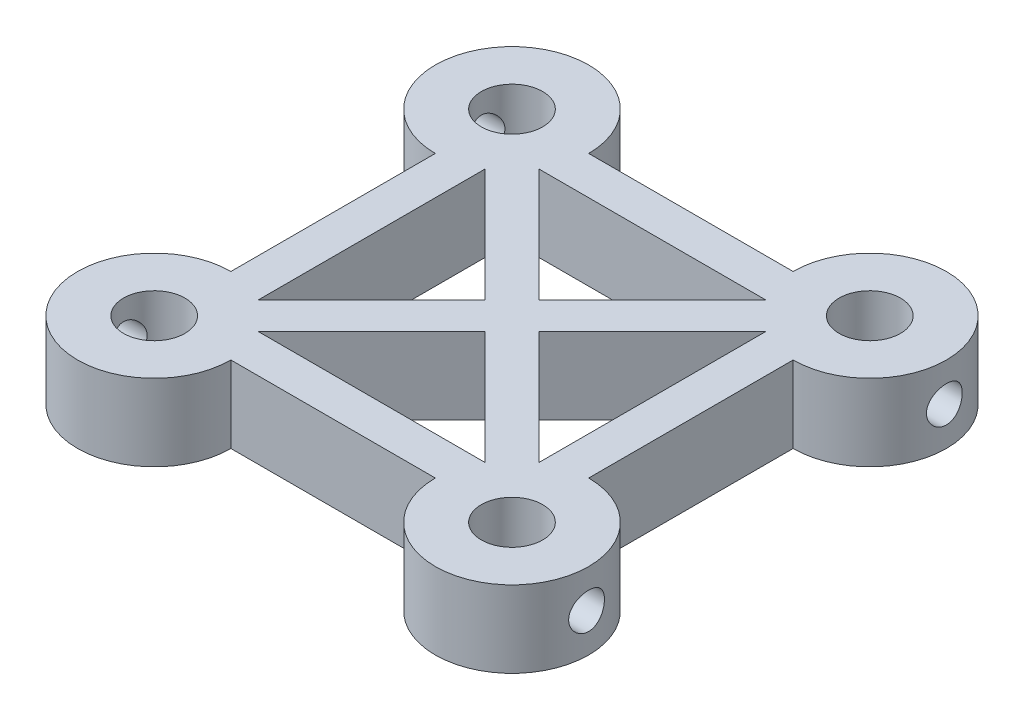
SolidWorks part; units mm, degrees
ref_plane "Front Plane" through (0, 0, 0) normal (0, 0, 1) x (1, 0, 0)
ref_plane "Top Plane" through (0, 0, 0) normal (0, 1, 0) x (1, 0, 0)
ref_plane "Right Plane" through (0, 0, 0) normal (1, 0, 0) x (0, 0, -1)
sketch "Sketch1" plane through (0, 0, 0) normal (0, 1, 0) x (1, 0, 0)
  line L0 (14, 28) -> (14, 0) construction
  line L1 (0, 0) -> (28, 0)
  line L2 (0, 0) -> (0, 28)
  line L3 (0, 28) -> (28, 28)
  line L4 (28, 0) -> (28, 28)
  line L5 (0, 14) -> (28, 14) construction
  point P9 (14, 14)
  dimension "D1" = 28
extrude "Boss-Extrude1" add sketch "Sketch1" along normal blind 6
sketch "Sketch2" plane through (0, 6, 0) normal (0, 1, 0) x (1, 0, 0)
  line L0 (14, 28) -> (14, -49972) construction
  line L1 (28, 28) -> (0, 28) construction
  line L2 (0, 14) -> (50000, 14) construction
  line L3 (0, 28) -> (0, 0) construction
  circle A0 centre (0, 28) radius 6
  circle A1 centre (28, 28) radius 6
  circle A2 centre (28, 0) radius 6
  circle A3 centre (0, 0) radius 6
  point P7 (14, 28)
  point P12 (0, 14)
  dimension "D1" = 12
extrude "Boss-Extrude2" add sketch "Sketch2" against normal up to surface (6 mm away) up to face at (14, 0, -14)
sketch "Sketch3" plane through (0, 6, 0) normal (0, 1, 0) x (1, 0, 0)
  line L0 (0, 0) -> (0, 28) construction
  line L1 (0, 28) -> (28, 28) construction
  line L2 (0, 0) -> (0, 28) construction
  line L3 (0, 28) -> (28, 28) construction
  line L4 (14, 28) -> (14, -49972) construction
  line L5 (0, 14) -> (50000, 14) construction
  circle A0 centre (0, 28) radius 2.4
  circle A1 centre (28, 28) radius 2.4
  circle A2 centre (28, 0) radius 2.4
  circle A3 centre (0, 0) radius 2.4
  point P6 (14, 28)
  point P9 (0, 14)
  dimension "D1" = 4.8
extrude "Cut-Extrude1" cut sketch "Sketch3" against normal through all
sketch "Sketch4" plane through (0, 6, 0) normal (0, 1, 0) x (1, 0, 0)
  line L0 (14, 28) -> (14, 0) construction
  line L1 (0, 14) -> (28, 14) construction
  line L2 (28, 0) -> (28, 28) construction
  line L3 (0, 0) -> (28, 0) construction
  line L4 (0, 0) -> (0, 28) construction
  line L5 (0, 28) -> (28, 28) construction
  line L6 (14, 28) -> (14, 0) construction
  line L7 (0, 14) -> (28, 14) construction
  line L8 (28, 0) -> (28, 28) construction
  line L9 (0, 0) -> (28, 0) construction
  line L10 (0, 0) -> (0, 28) construction
  line L11 (0, 28) -> (28, 28) construction
  line L12 (0, 28) -> (28, 0) construction
  line L13 (3, 25) -> (25, 25)
  line L14 (3, 25) -> (3, 3)
  line L15 (3, 3) -> (25, 3)
  line L16 (25, 25) -> (25, 3)
  line L17 (0, 0) -> (28, 28) construction
  line L18 (3, 22.8787) -> (11.8787, 14)
  line L19 (5.1213, 25) -> (14, 16.1213)
  line L20 (3, 5.1213) -> (11.8787, 14)
  line L21 (5.1213, 3) -> (14, 11.8787)
  line L22 (14, 16.1213) -> (22.8787, 25)
  line L23 (14, 11.8787) -> (22.8787, 3)
  line L24 (16.1213, 14) -> (25, 22.8787)
  line L25 (16.1213, 14) -> (25, 5.1213)
  point P12 (14, 25)
  point P13 (3, 14)
  dimension "D1" = 3
  dimension "D2" = 3
extrude "Cut-Extrude2" cut sketch "Sketch4" against normal blind 10 contours L14 L20 L18 | L19 L22 L13 | L24 L25 L16 | L23 L21 L15
sketch "Sketch5" plane through (28, 0, 0) normal (1, 0, 0) x (0, 0, -1)
  line L0 (28, 6) -> (28, 0) construction
  line L1 (0, 0) -> (0, 6) construction
  line L2 (28, 6) -> (28, 0) construction
  line L3 (0, 0) -> (0, 6) construction
  circle A0 centre (0, 3) radius 1.4
  circle A1 centre (28, 3) radius 1.4
  point P9 (0, 3)
  point P11 (28, 3)
  dimension "D1" = 2.8
sketch "Sketch6" plane through (0, 0, 0) normal (-1, 0, 0) x (0, 0, 1)
  circle A0 centre (-28, 3) radius 1.4 construction
  circle A1 centre (0, 3) radius 1.4 construction
  circle A2 centre (-28, 3) radius 1.4
  circle A3 centre (0, 3) radius 1.4
extrude "Cut-Extrude3" cut sketch "Sketch5" along normal blind 10
extrude "Cut-Extrude4" cut sketch "Sketch6" along normal blind 10
equation "\"TrackLength\"= 150"
equation "\"MarbleWidth\"= 13"
equation "\"MarbleTrackWidth\"= \"MarbleWidth\" - 1"
equation "\"TrackWidth\"= \"MarbleTrackWidth\" + ( 2 * 4 )"
equation "\"MarbleTrackLength\"= \"TrackLength\" - ( 2 * 8 )"
equation "\"MountWidth\"= \"TrackWidth\" + 8"
equation "\"D1@Sketch1\"= \"MountWidth\""
equation "\"RampDepth\"=6"
equation "\"RampAngle\"= 10"
equation "\"RampHeight\"= ( \"MountWidth\" * tan ( \"RampAngle\" ) ) + \"RampDepth\""
equation "\"MountWidth\"= \"TrackWidth\" + 10"
equation "\"MountLength\"=66.6651"
